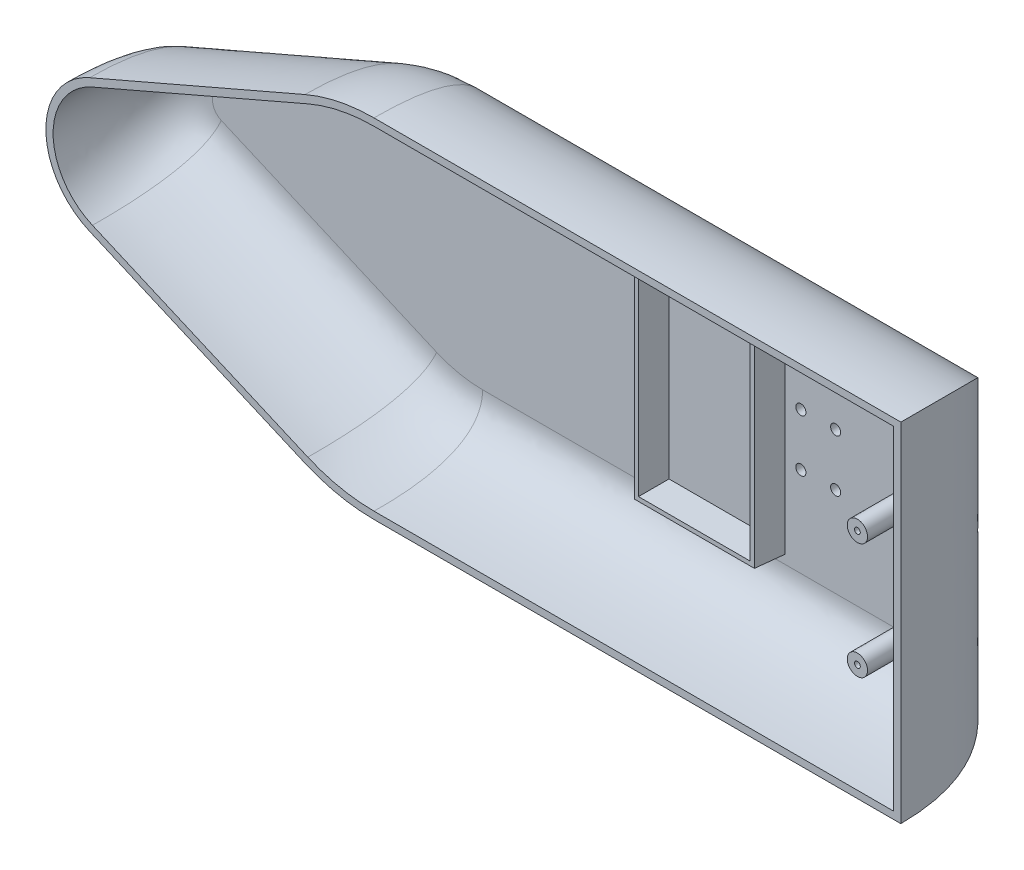
SolidWorks part; units mm, degrees
ref_plane "Plan de face" through (0, 0, 0) normal (0, 0, 1) x (1, 0, 0)
ref_plane "Plan de dessus" through (0, 0, 0) normal (0, 1, 0) x (1, 0, 0)
ref_plane "Plan de droite" through (0, 0, 0) normal (1, 0, 0) x (0, 0, -1)
sketch "Esquisse1" plane through (0, 0, 0) normal (0, 0, 1) x (1, 0, 0)
  line L0 (-12.7111, 35.4688) -> (-100.8999, 35.4688) construction
  line L1 (149.1001, 75.4688) -> (-12.7111, 75.4688)
  line L2 (149.1001, 75.4688) -> (149.1001, -4.5312)
  line L3 (149.1001, -4.5312) -> (-12.7111, -4.5313)
  line L4 (-12.7111, 75.4688) -> (-12.7111, 35.4688) construction
  line L5 (-102.8843, 40.0581) -> (-28.5862, 72.1836)
  line L6 (-102.8843, 30.8794) -> (-28.5862, -1.2461)
  line L7 (-12.7111, 35.4688) -> (-12.7111, -4.5313) construction
  arc A0 (-102.8843, 40.0581) -> (-102.8843, 30.8794) centre (-100.8999, 35.4688) ccw
  arc A1 (-28.5862, -1.2461) -> (-12.7111, -4.5313) centre (-12.7111, 35.4688) ccw
  arc A2 (-12.7111, 75.4688) -> (-28.5862, 72.1836) centre (-12.7111, 35.4688) ccw
  dimension "D3" = 10
  dimension "D1" = 250
  dimension "D2" = 80
extrude "Boss.-Extru.1" add sketch "Esquisse1" along normal blind 2.5
sketch "Esquisse3" plane through (0, 0, 2.5) normal (0, 0, 1) x (1, 0, 0)
  line L0 (149.1001, 35.4688) -> (-105.8999, 35.4688) construction
  line L1 (149.1001, -4.5312) -> (149.1001, 75.4688) construction
  line L2 (109.1001, 66.3622) -> (109.1001, 22.1054) construction
  line L3 (97.1001, 66.3622) -> (97.1001, 22.1054) construction
  arc A0 (-102.8843, 40.0581) -> (-102.8843, 30.8794) centre (-100.8999, 35.4688) ccw construction
  circle A1 centre (97.1001, 44.4688) radius 1.75
  circle A2 centre (97.1001, 26.4688) radius 1.75
  circle A3 centre (109.1001, 26.4688) radius 1.75
  circle A4 centre (109.1001, 44.4688) radius 1.75
  dimension "D1" = 3.5
  dimension "D2" = 3.5
  dimension "D3" = 3.5
  dimension "D4" = 3.5
  dimension "D7" = 9
  dimension "D8" = 9
  dimension "D9" = 9
  dimension "D5" = 12
  dimension "D6" = 9
  dimension "D10" = 40
extrude "Enlèv. mat.-Extru.1" cut sketch "Esquisse3" against normal up to next
sketch "Esquisse4" plane through (0, 0, 2.5) normal (0, 0, -1) x (-1, 0, 0)
  line L0 (-149.1001, 35.4688) -> (-3.0389, 35.4688) construction
  line L1 (-51.6001, 0.9688) -> (-89.1001, 0.9688)
  line L2 (-51.6001, 0.9688) -> (-51.6001, 67.4688)
  line L3 (-54.1001, 69.9688) -> (-86.6001, 69.9688)
  line L5 (-149.1001, -4.5312) -> (-149.1001, 75.4688) construction
  line L7 (-49.1001, -1.5312) -> (-91.6001, -1.5312)
  line L8 (-49.1001, -1.5312) -> (-49.1001, 67.4688)
  line L9 (-54.1001, 72.4688) -> (-86.6001, 72.4688)
  line L10 (-91.6001, -1.5312) -> (-91.6001, 67.4688)
  line L11 (-89.1001, 0.9688) -> (-89.1001, 67.4688)
  line L13 (-49.1001, 67.4688) -> (-51.6001, 67.4688)
  line L14 (-54.1001, 72.4688) -> (-54.1001, 69.9688)
  line L17 (-91.6001, 67.4688) -> (-89.1001, 67.4688)
  line L18 (-86.6001, 72.4688) -> (-86.6001, 69.9688)
  circle A0 centre (-97.1001, 26.4688) radius 1.75 construction
  point P3 (-70.3996, 0.9688)
  point P4 (-51.6001, 35.4688)
  point P14 (-70.3501, 69.9688)
  dimension "D2" = 2.5
  dimension "D3" = 2.5
  dimension "D4" = 2.5
  dimension "D5" = 34.5
  dimension "D6" = 5.5
  dimension "D7" = 2.5
  dimension "D8" = 32.5
  dimension "D9" = 2.5
  dimension "D10" = 2.5
  dimension "D11" = 34.5
  dimension "D12" = 2.5
  dimension "D13" = 2.5
extrude "Boss.-Extru.2" add sketch "Esquisse4" against normal blind 10 draft 3
sketch "Esquisse5" plane through (0, 0, 2.5) normal (0, 0, 1) x (1, 0, 0)
  line L1 (149.1001, 75.4688) -> (-12.7111, 75.4688) construction
  line L2 (-28.5862, 72.1836) -> (-102.8843, 40.0581) construction
  line L3 (-102.8843, 30.8794) -> (-28.5862, -1.2461) construction
  line L4 (-12.7111, -4.5313) -> (149.1001, -4.5312) construction
  line L5 (149.1001, -4.5312) -> (149.1001, 75.4688) construction
  line L6 (149.1001, 75.4688) -> (-12.7111, 75.4688)
  line L7 (-28.5862, 72.1836) -> (-102.8843, 40.0581)
  line L8 (-102.8843, 30.8794) -> (-28.5862, -1.2461)
  line L9 (-12.7111, -4.5313) -> (149.1001, -4.5312)
  line L10 (149.1001, -4.5312) -> (149.1001, 75.4688)
  arc A0 (-12.7111, 75.4688) -> (-28.5862, 72.1836) centre (-12.7111, 35.4688) ccw construction
  arc A1 (-102.8843, 40.0581) -> (-102.8843, 30.8794) centre (-100.8999, 35.4688) ccw construction
  arc A2 (-28.5862, -1.2461) -> (-12.7111, -4.5313) centre (-12.7111, 35.4688) ccw construction
  arc A3 (-12.7111, 75.4688) -> (-28.5862, 72.1836) centre (-12.7111, 35.4688) ccw
  arc A4 (-102.8843, 40.0581) -> (-102.8843, 30.8794) centre (-100.8999, 35.4688) ccw
  arc A5 (-28.5862, -1.2461) -> (-12.7111, -4.5313) centre (-12.7111, 35.4688) ccw
sketch "Esquisse7" plane through (149.1001, 0, 0) normal (1, 0, 0) x (0, 0, -1)
  line L0 (0, -4.5312) -> (0, 75.4688) construction
  line L4 (-2.5, 75.4688) -> (0, 75.4688) construction
  line L5 (-2.5, 75.4688) -> (-2.5, 72.1836) construction
  line L6 (-2.5, 75.4688) -> (0, 75.4688)
  line L7 (-40, 95.4688) -> (-40, 92.9688)
  spline S0 degree 3 poles (0, 75.4688) (0, 86.4116) (-9.0996, 95.407) (-40, 95.4688) knots 0 0 0 0 1 1 1 1
  spline S1 degree 3 poles (-40, 92.9688) (-36.8249, 92.9688) (-2.5, 94.5136) (-2.5, 75.4687) knots 0 0 0 0 1 1 1 1
  dimension "D2" = 20
  dimension "D1" = 40
  dimension "D3" = 2.5
sweep "Balayage1" add profiles "Esquisse7" path "Esquisse5"
sketch "Esquisse8" plane through (0, 0, 0) normal (0, 0, -1) x (-1, 0, 0)
  line L0 (-149.1001, 35.4688) -> (-183.6058, 35.4688) construction
  line L1 (-149.1001, -4.5312) -> (-149.1001, 75.4688) construction
  line L2 (-154.1001, 64.6793) -> (-154.1001, 3.4231) construction
  circle A0 centre (-154.1001, 55.4688) radius 1
  circle A1 centre (-154.1001, 15.4688) radius 1
  circle A2 centre (-109.1001, 26.4688) radius 1.75 construction
  dimension "D3" = 2
  dimension "D4" = 2
  dimension "D1" = 20
  dimension "D2" = 20
  dimension "D5" = 45
extrude "Enlèv. mat.-Extru.2" cut sketch "Esquisse8" against normal up to next
sketch "Esquisse9" plane through (0, 0, 40) normal (0, 0, 1) x (1, 0, 0)
  circle A0 centre (154.1001, 55.4688) radius 1
  circle A1 centre (154.1001, 15.4688) radius 1
  circle A2 centre (154.1001, 15.4688) radius 3.5
  circle A3 centre (154.1001, 55.4688) radius 3.5
  dimension "D1" = 2.5
  dimension "D2" = 2.5
  dimension "D3" = 2
  dimension "D4" = 2
extrude "Boss.-Extru.3" add sketch "Esquisse9" against normal up to surface (36.1328 mm away)
